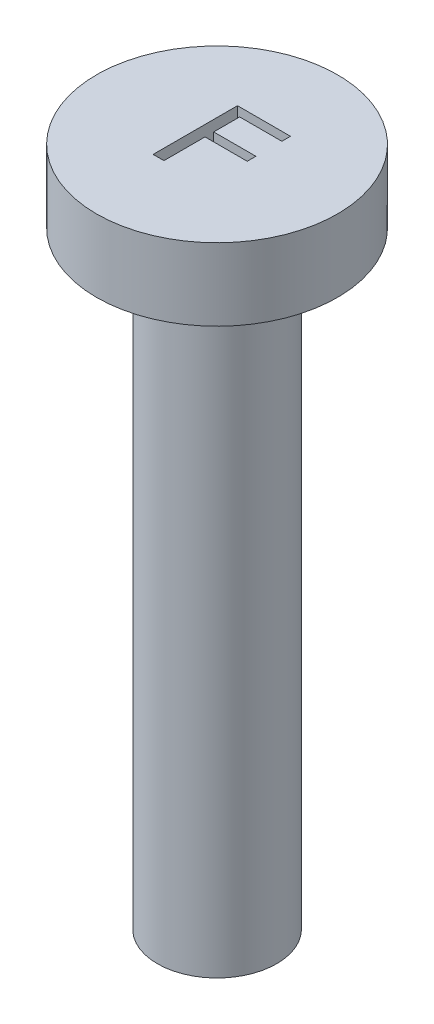
SolidWorks part; units mm, degrees
ref_plane "Front Plane" through (0, 0, 0) normal (0, 0, 1) x (1, 0, 0)
ref_plane "Top Plane" through (0, 0, 0) normal (0, 1, 0) x (1, 0, 0)
ref_plane "Right Plane" through (0, 0, 0) normal (1, 0, 0) x (0, 0, -1)
sketch "Sketch1" plane through (0, 0, 0) normal (0, 1, 0) x (1, 0, 0)
  circle A0 centre (0, 0) radius 2.475
  dimension "D1" = 4.95
extrude "Boss-Extrude1" add sketch "Sketch1" along normal blind 25.2
sketch "Sketch2" plane through (0, 25.2, 0) normal (0, 1, 0) x (1, 0, 0)
  circle A0 centre (0, 0) radius 5
  dimension "D1" = 10
extrude "Boss-Extrude2" add sketch "Sketch2" along normal blind 3
sketch "Sketch4" plane through (0, 0, 0) normal (0, -1, 0) x (1, 0, 0)
  line L0 (0, 2.475) -> (0, -2.475) construction
  circle A0 centre (0, 0) radius 2.475 construction
sketch "Sketch8" plane through (0, 0, 0) normal (0, -1, 0) x (1, 0, 0)
  circle A0 centre (0, 0) radius 2.5
hole_wizard "M2.5x0.45 Tapped Hole2" positions "Sketch13" profile "Sketch14" tap size "M2.5x0.45" standard "BSI"
sketch "Sketch13" plane through (0, 0, 0) normal (0, -1, 0) x (-1, 0, 0)
  point P0 (0, 0)
sketch "Sketch14" plane through (0, 0, 0) normal (1, 0, 0) x (0, 0, -1)
  line L0 (0, 0) -> (0, 7.8659)
  line L1 (0, 7.8659) -> (1.025, 7.25)
  line L2 (1.025, 7.25) -> (1.025, 0)
  line L5 (1.025, 0) -> (0, 0)
  line L10 (0, 7.8659) -> (-1.025, 7.25) construction
  line L11 (0, -6.35) -> (0, 107.95) construction
  dimension "Tap Drill Dia." = 2.05
  dimension "Tap Drill Depth" = 7.25
  dimension "Drill Angle" = 118
cosmetic thread "Hole Thread2" parameters "D1"=5, "D2"=2.5
sketch "Sketch15" plane through (0, 28.2, 0) normal (0, 1, 0) x (1, 0, 0)
  line L0 (-4.7068, -1.687) -> (4.7068, -1.687) construction
  circle A0 centre (0, 0) radius 5 construction
  text T0 "F" font "Century Gothic" height 3.5
extrude "Cut-Extrude1" cut sketch "Sketch15" against normal blind 1
